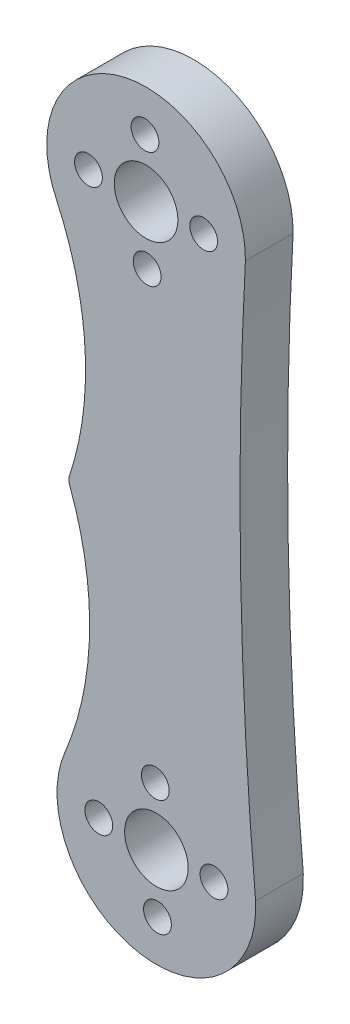
SolidWorks part; units mm, degrees
material "ABS"
ref_plane "Front Plane" through (0, 0, 0) normal (0, 0, 1) x (1, 0, 0)
ref_plane "Top Plane" through (0, 0, 0) normal (0, 1, 0) x (1, 0, 0)
ref_plane "Right Plane" through (0, 0, 0) normal (1, 0, 0) x (0, 0, -1)
sketch "Sketch1" plane through (0, 0, 0) normal (0, 0, 1) x (1, 0, 0)
  line L1 (-15, -50) -> (15, -50)
  line L2 (-15, -50) -> (-15, 50)
  line L3 (-15, 50) -> (15, 50)
  line L4 (15, -50) -> (15, 50)
  line L5 (-15, -50) -> (15, 50) construction
  line L6 (-15, 50) -> (15, -50) construction
  point P0 (0, 0)
  dimension "D1" = 100
  dimension "D2" = 30
extrude "Boss-Extrude1" add sketch "Sketch1" along normal blind 6
sketch "Sketch2" plane through (0, 0, 0) normal (0, 0, -1) x (-1, 0, 0)
  line L0 (-15, 50) -> (15, 50)
  line L1 (15, 50) -> (15, -50)
  line L2 (15, -50) -> (-15, -50)
  line L3 (-15, -50) -> (-15, 50)
  arc A0 (-11.5325, 35.4338) -> (13.1458, 32.8353) centre (0.9658, 35.6453) cw
  arc A1 (13.4636, 35.4133) -> (-11.5321, 35.8772) centre (0.9658, 35.6453) ccw construction
  arc A2 (12.3021, 30.3787) -> (13.4636, 35.4133) centre (0.9658, 35.6453) ccw construction
  arc A3 (13.1458, 32.8353) -> (12.3021, 30.3787) centre (0.9658, 35.6453) cw
  arc A4 (12.3021, 30.3787) -> (10.604, 0.9581) centre (48.5784, 13.5255) ccw
  arc A5 (8.5853, 14.2678) -> (10.604, 0.9581) centre (48.5784, 13.5255) ccw construction
  arc A6 (10.604, 0.9581) -> (10.5855, -0.037) centre (9.1799, 0.4868) cw
  arc A7 (10.5855, -0.037) -> (8.0744, -13.2627) centre (48.0675, -14.0049) ccw construction
  arc A8 (-12.815, -33.6676) -> (11.1908, -29.5004) centre (-0.3332, -34.3427) ccw
  arc A9 (-12.8311, -34.1107) -> (12.1646, -34.5746) centre (-0.3332, -34.3427) ccw construction
  arc A10 (12.1646, -34.5746) -> (11.1908, -29.5004) centre (-0.3332, -34.3427) ccw construction
  arc A11 (11.1908, -29.5004) -> (10.5855, -0.037) centre (48.0675, -14.0049) cw
  arc A13 (-11.5325, 35.4338) -> (-12.815, -33.6676) centre (-492.0571, 9.7897) cw
  arc A14 (-12.7832, -33.2253) -> (-12.8311, -34.1107) centre (-0.3332, -34.3427) ccw construction
  arc A15 (8.0744, -13.2627) -> (11.1908, -29.5004) centre (48.0675, -14.0049) ccw construction
  arc A16 (12.3021, 30.3787) -> (13.4636, 35.4133) centre (0.9658, 35.6453) ccw construction
  circle A17 centre (0.9658, 35.6453) radius 4
  circle A18 centre (1.1003, 42.894) radius 1.75
  circle A19 centre (8.2145, 35.5107) radius 1.75
  circle A20 centre (-6.283, 35.7798) radius 1.75
  circle A21 centre (0.8312, 28.3965) radius 1.75
  circle A22 centre (-0.3332, -34.3427) radius 4
  circle A23 centre (-0.1987, -27.0939) radius 1.75
  circle A24 centre (6.9155, -34.4772) radius 1.75
  circle A25 centre (-0.4677, -41.5914) radius 1.75
  circle A26 centre (-7.582, -34.2081) radius 1.75
  line M5 (-15, 50) -> (-15, -50)
  line M6 (-15, -50) -> (15, -50)
  line M7 (15, -50) -> (15, 50)
  line M8 (15, 50) -> (-15, 50)
extrude "Cut-Extrude1" cut sketch "Sketch2" against normal blind 6 contours A13 A0 A3 A4 A6 A11 A8 M8 M5 M6 M7 | A17 | A18 | A19 | A21 | A20 | A22 | A23 | A24 | A26 | A25
